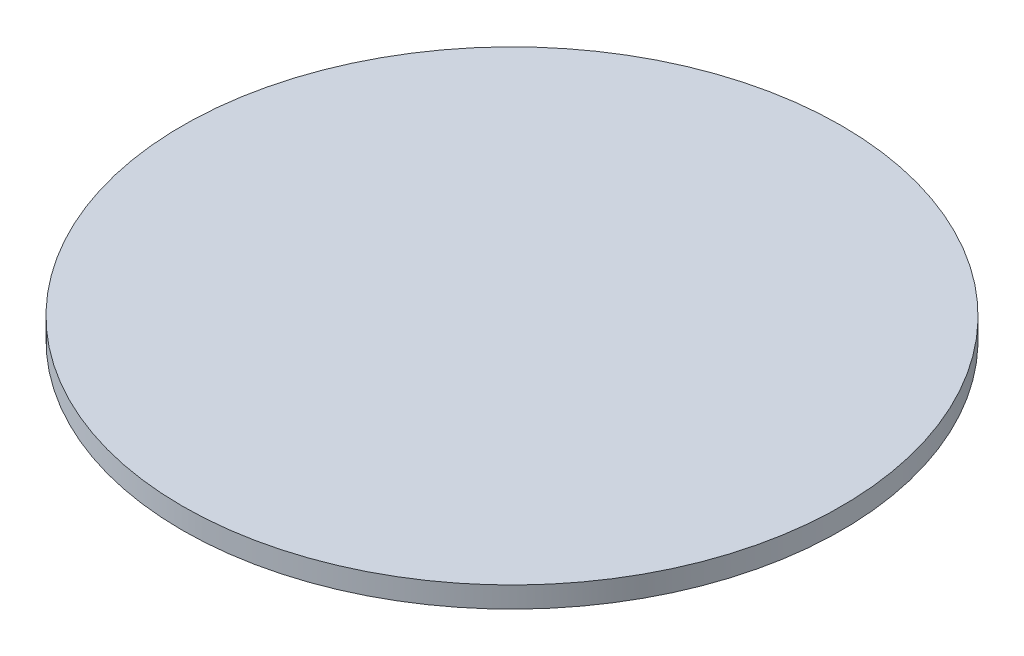
SolidWorks part; units mm, degrees
ref_plane "Спереди" through (0, 0, 0) normal (0, 0, 1) x (1, 0, 0)
ref_plane "Сверху" through (0, 0, 0) normal (0, 1, 0) x (1, 0, 0)
ref_plane "Справа" through (0, 0, 0) normal (1, 0, 0) x (0, 0, -1)
sketch "Эскиз1" plane through (0, 0, 0) normal (0, 1, 0) x (1, 0, 0)
  circle A0 centre (0, 0) radius 15.75
  dimension "D1" = 31.5
extrude "Бобышка-Вытянуть1" add sketch "Эскиз1" along normal blind 1
